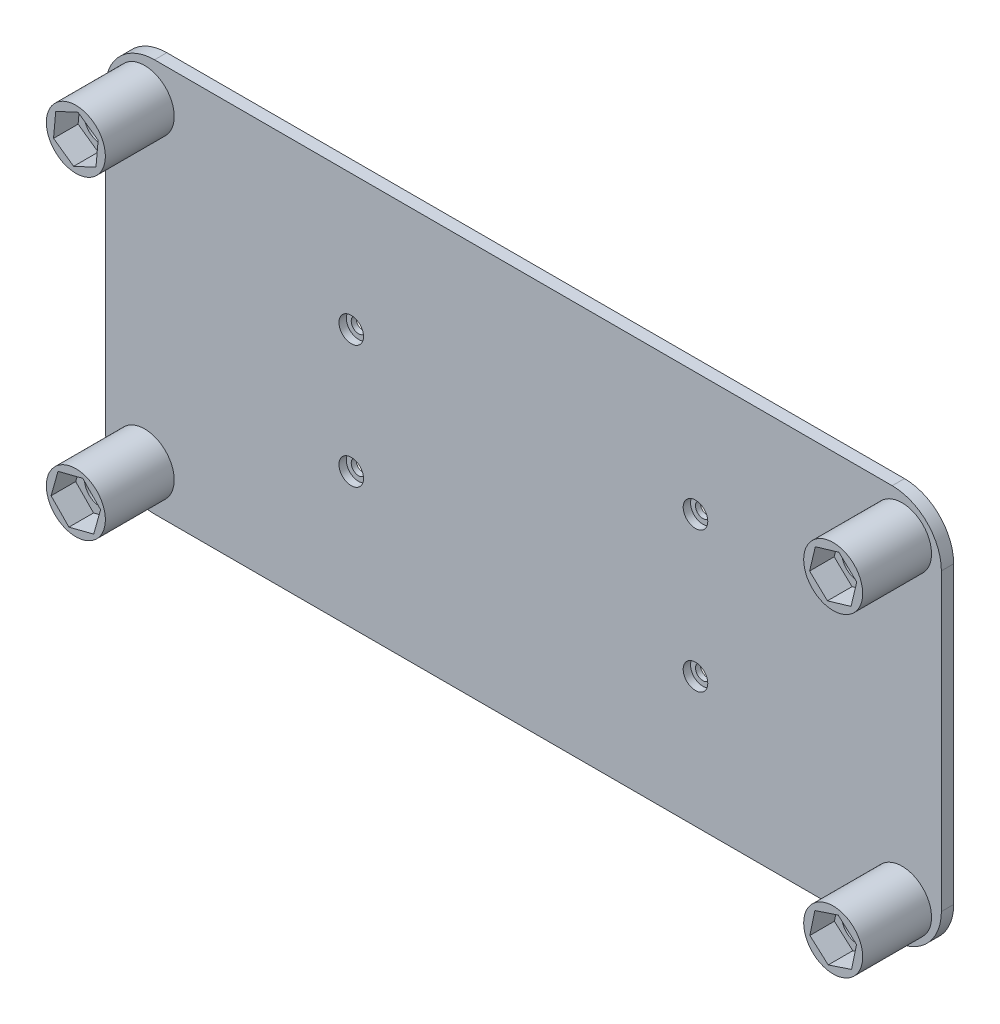
SolidWorks part; units mm, degrees
ref_plane "前视基准面" through (0, 0, 0) normal (0, 0, 1) x (1, 0, 0)
ref_plane "上视基准面" through (0, 0, 0) normal (0, 1, 0) x (1, 0, 0)
ref_plane "右视基准面" through (0, 0, 0) normal (1, 0, 0) x (0, 0, -1)
sketch "草图1" plane through (0, 0, 0) normal (0, 0, 1) x (1, 0, 0)
  line L1 (-72.5741, 35.4874) -> (77.4259, 35.4874)
  line L2 (-82.5741, 25.4874) -> (-82.5741, -34.5126)
  line L3 (-72.5741, -44.5126) -> (77.4259, -44.5126)
  line L4 (87.4259, 25.4874) -> (87.4259, -34.5126)
  arc A0 (-72.5741, 35.4874) -> (-82.5741, 25.4874) centre (-72.5741, 25.4874) ccw
  arc A1 (-72.5741, -44.5126) -> (-82.5741, -34.5126) centre (-72.5741, -34.5126) cw
  arc A2 (87.4259, 25.4874) -> (77.4259, 35.4874) centre (77.4259, 25.4874) ccw
  arc A3 (87.4259, -34.5126) -> (77.4259, -44.5126) centre (77.4259, -34.5126) cw
  dimension "D1" = 10
  dimension "D2" = 10
  dimension "D3" = 10
  dimension "D4" = 10
  dimension "D5" = 80
  dimension "D6" = 170
extrude "凸台-拉伸1" add sketch "草图1" along normal blind 2.5
ref_plane "for screw hole" through (0, 0, 2.5) normal (0, 0, 1) x (1, 0, 0)
sketch "草图2" plane through (0, 0, 2.5) normal (0, 0, 1) x (1, 0, 0)
  line L0 (77.4259, 35.4874) -> (-72.5741, 35.4874) construction
  line L1 (-82.5741, 25.4874) -> (-82.5741, -34.5126) construction
  circle A0 centre (-32.5741, 7.9874) radius 1.5
  circle A1 centre (-32.5741, -17.0126) radius 1.5
  circle A2 centre (37.4259, 10.4502) radius 1.5
  circle A3 centre (37.4259, -18.0901) radius 1.5
  point P16 (-71.5646, -35.7491)
  point P17 (77.4698, 24.988)
  point P18 (77.4698, -35.7491)
  dimension "D2" = 3
  dimension "D3" = 3
  dimension "D4" = 3
  dimension "D8" = 27.5
  dimension "D9" = 50
  dimension "D10" = 50
  dimension "D11" = 3
  dimension "D5" = 70
  dimension "D6" = 70
  dimension "D7" = 25
extrude "切除-拉伸1" cut sketch "草图2" against normal blind 10 and the other way blind 42
ref_plane "for outer screw hole" through (0, 0, 2.5) normal (0, 0, 1) x (1, 0, 0)
sketch "草图3" plane through (0, 0, 2.5) normal (0, 0, 1) x (1, 0, 0)
  circle A0 centre (-32.5741, 7.9874) radius 2.5
  circle A1 centre (37.4259, 10.4502) radius 2.5
  circle A2 centre (37.4259, -18.0901) radius 2.5
  circle A3 centre (-32.5741, -17.0126) radius 2.5
  dimension "D1" = 5
  dimension "D2" = 5
  dimension "D3" = 5
  dimension "D4" = 5
extrude "切除-拉伸2" cut sketch "草图3" against normal blind 1.5
ref_plane "for stands" through (0, 0, 2.5) normal (0, 0, 1) x (1, 0, 0)
sketch "草图7" plane through (0, 0, 2.5) normal (0, 0, 1) x (1, 0, 0)
  line L0 (77.4259, 35.4874) -> (-72.5741, 35.4874) construction
  line L1 (-82.5741, 25.4874) -> (-82.5741, -34.5126) construction
  line L2 (-72.5741, -44.5126) -> (77.4259, -44.5126) construction
  line L3 (87.4259, -34.5126) -> (87.4259, 25.4874) construction
  circle A0 centre (-74.5741, 27.4874) radius 6
  circle A1 centre (-74.5741, -36.5126) radius 6
  circle A2 centre (79.4259, 27.4874) radius 6
  circle A3 centre (79.4259, -36.5126) radius 6
  point P12 (0, 0)
  point P13 (0, 0)
  point P14 (-70.2304, -44.5126)
  point P18 (-68.2335, -44.5126)
  dimension "D1" = 12
  dimension "D2" = 12
  dimension "D3" = 12
  dimension "D4" = 12
  dimension "D7" = 8
  dimension "D5" = 8
  dimension "D6" = 8
  dimension "D8" = 8
  dimension "D9" = 8
  dimension "D10" = 8
  dimension "D11" = 8
  dimension "D12" = 8
extrude "凸台-拉伸4" add sketch "草图7" along normal blind 14
ref_plane "button left hole" through (0, 0, 16.5) normal (0, 0, 1) x (1, 0, 0)
ref_plane "up left hole" through (0, 0, 16.5) normal (0, 0, 1) x (1, 0, 0)
ref_plane "up right hole" through (0, 0, 16.5) normal (0, 0, 1) x (1, 0, 0)
ref_plane "button right hole" through (0, 0, 16.5) normal (0, 0, 1) x (1, 0, 0)
sketch "草图9" plane through (0, 0, 16.5) normal (0, 0, 1) x (1, 0, 0)
  line L1 (-70.9446, -40.2262) -> (-69.5433, -35.2262)
  line L2 (-69.5433, -35.2262) -> (-73.1728, -31.5126)
  line L3 (-73.1728, -31.5126) -> (-78.2036, -32.7991)
  line L4 (-78.2036, -32.7991) -> (-79.6049, -37.7991)
  line L5 (-79.6049, -37.7991) -> (-75.9754, -41.5126)
  line L6 (-75.9754, -41.5126) -> (-70.9446, -40.2262)
  circle A0 centre (-74.5741, -36.5126) radius 4.497 construction
  circle A1 centre (-74.5741, -36.5126) radius 6 construction
  dimension "D1" = 5
  dimension "D2" = 0
extrude "button left nut " cut sketch "草图9" against normal blind 5
sketch "草图10" plane through (0, 0, 16.5) normal (0, 0, 1) x (1, 0, 0)
  line L1 (-70.4846, 24.6106) -> (-70.038, 29.5906)
  line L2 (-70.038, 29.5906) -> (-74.1275, 32.4674)
  line L3 (-74.1275, 32.4674) -> (-78.6636, 30.3642)
  line L4 (-78.6636, 30.3642) -> (-79.1102, 25.3842)
  line L5 (-79.1102, 25.3842) -> (-75.0207, 22.5074)
  line L6 (-75.0207, 22.5074) -> (-70.4846, 24.6106)
  circle A0 centre (-74.5741, 27.4874) radius 4.3301 construction
  circle A1 centre (-74.5741, 27.4874) radius 6 construction
  dimension "D1" = 5
  dimension "D2" = 0
extrude "up left nut" cut sketch "草图10" against normal blind 5
sketch "草图11" plane through (0, 0, 16.5) normal (0, 0, 1) x (1, 0, 0)
  line L1 (83.0542, 24.0471) -> (84.2194, 28.9094)
  line L2 (84.2194, 28.9094) -> (80.5911, 32.3497)
  line L3 (80.5911, 32.3497) -> (75.7976, 30.9277)
  line L4 (75.7976, 30.9277) -> (74.6324, 26.0653)
  line L5 (74.6324, 26.0653) -> (78.2607, 22.6251)
  line L6 (78.2607, 22.6251) -> (83.0542, 24.0471)
  circle A0 centre (79.4259, 27.4874) radius 4.3301 construction
  circle A2 centre (79.4259, 27.4874) radius 6 construction
  dimension "D2" = 0
  dimension "D1" = 5
extrude "up right nut" cut sketch "草图11" against normal blind 5
sketch "草图12" plane through (0, 0, 16.5) normal (0, 0, 1) x (1, 0, 0)
  line L1 (83.1629, -39.8344) -> (84.1712, -34.9371)
  line L2 (84.1712, -34.9371) -> (80.4341, -31.6153)
  line L3 (80.4341, -31.6153) -> (75.6888, -33.1908)
  line L4 (75.6888, -33.1908) -> (74.6806, -38.0881)
  line L5 (74.6806, -38.0881) -> (78.4176, -41.4099)
  line L6 (78.4176, -41.4099) -> (83.1629, -39.8344)
  circle A0 centre (79.4259, -36.5126) radius 4.3301 construction
  circle A1 centre (79.4259, -36.5126) radius 6 construction
  dimension "D2" = 0
  dimension "D1" = 5
extrude "button right nut" cut sketch "草图12" against normal blind 5
ref_plane "基准面13" through (0, 0, 16.5) normal (0, 0, 1) x (1, 0, 0)
ref_plane "基准面14" through (0, 0, 16.5) normal (0, 0, 1) x (1, 0, 0)
ref_plane "基准面15" through (0, 0, 16.5) normal (0, 0, 1) x (1, 0, 0)
ref_plane "基准面16" through (0, 0, 16.5) normal (0, 0, 1) x (1, 0, 0)
sketch "草图13" plane through (0, 0, 16.5) normal (0, 0, 1) x (1, 0, 0)
  circle A0 centre (-74.5741, -36.5126) radius 3.25
  dimension "D1" = 6.5
extrude "切除-拉伸7" cut sketch "草图13" against normal blind 13
sketch "草图15" plane through (0, 0, 16.5) normal (0, 0, 1) x (1, 0, 0)
  circle A0 centre (-74.5741, 27.4874) radius 3.25
  circle A1 centre (-74.5741, 27.4874) radius 6 construction
  dimension "D1" = 6.5
  dimension "D2" = 0
extrude "切除-拉伸8" cut sketch "草图15" against normal blind 13
sketch "草图16" plane through (0, 0, 16.5) normal (0, 0, 1) x (1, 0, 0)
  circle A0 centre (79.4259, 27.4874) radius 3.25
  dimension "D1" = 6.5
extrude "切除-拉伸9" cut sketch "草图16" against normal blind 13
sketch "草图17" plane through (0, 0, 16.5) normal (0, 0, 1) x (1, 0, 0)
  circle A0 centre (79.4259, -36.5126) radius 3.25
  circle A1 centre (79.4259, -36.5126) radius 6 construction
  point P4 (79.4259, -36.2982)
  point P5 (79.4259, -36.2982)
  point P6 (79.4259, -36.2982)
  point P7 (79.4259, -36.2982)
  point P8 (79.1933, -31.3796)
  dimension "D1" = 6.5
  dimension "D2" = 0
extrude "切除-拉伸10" cut sketch "草图17" against normal blind 13
